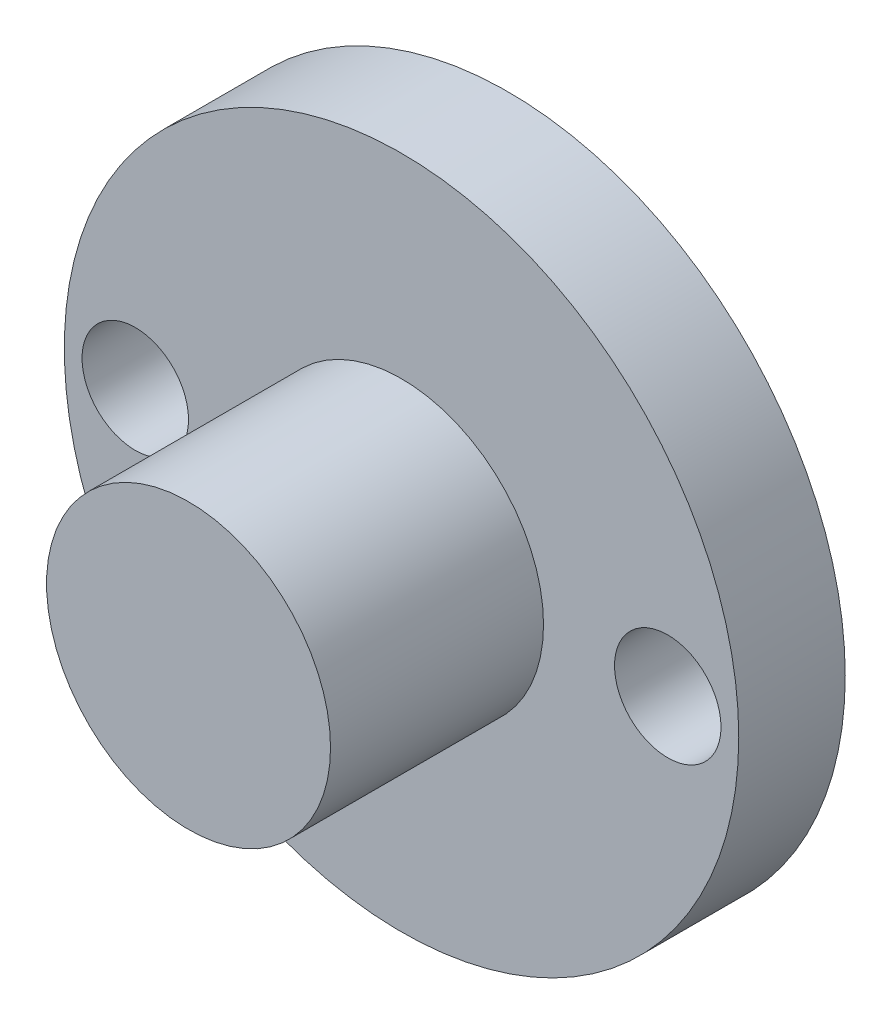
SolidWorks part; units mm, degrees
ref_plane "Alzado" through (0, 0, 0) normal (0, 0, 1) x (1, 0, 0)
ref_plane "Planta" through (0, 0, 0) normal (0, 1, 0) x (1, 0, 0)
ref_plane "Vista lateral" through (0, 0, 0) normal (1, 0, 0) x (0, 0, -1)
sketch "Croquis1" plane through (0, 0, 0) normal (0, 0, 1) x (1, 0, 0)
  circle A0 centre (0, 0) radius 9.5
extrude "Saliente-Extruir1" add sketch "Croquis1" along normal blind 3
sketch "Croquis2" plane through (0, 0, 3) normal (0, 0, 1) x (1, 0, 0)
  circle A0 centre (0, 0) radius 4
extrude "Saliente-Extruir2" add sketch "Croquis2" along normal blind 6
sketch "Croquis3" plane through (0, 0, 0) normal (0, 0, -1) x (-1, 0, 0)
  circle A0 centre (0, 0) radius 2.5
extrude "Saliente-Extruir3" add sketch "Croquis3" along normal blind 1.5
sketch "Croquis4" plane through (0, 0, 3) normal (0, 0, 1) x (1, 0, 0)
  line L0 (0, 0) -> (7.5, 0) construction
  line L1 (7.5, 0) -> (-7.5, 0) construction
  circle A0 centre (-7.5, 0) radius 1.5
  circle A1 centre (7.5, 0) radius 1.5
extrude "Cortar-Extruir1" cut sketch "Croquis4" against normal through all
